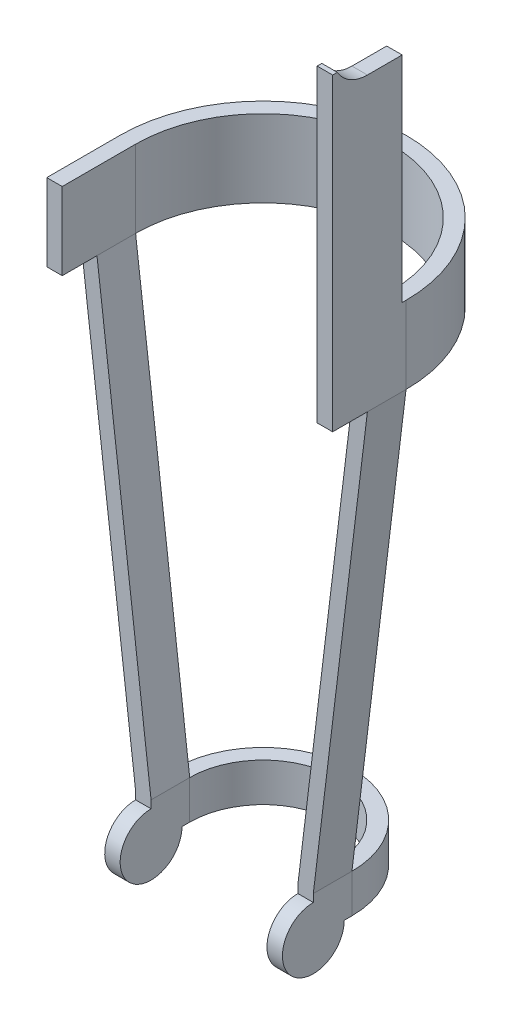
SolidWorks part; units mm, degrees
ref_plane "Front" through (0, 0, 0) normal (0, 0, 1) x (1, 0, 0)
ref_plane "Top" through (0, 0, 0) normal (0, 1, 0) x (1, 0, 0)
ref_plane "Right" through (0, 0, 0) normal (1, 0, 0) x (0, 0, -1)
sketch "草图1" plane through (0, 0, 0) normal (1, 0, 0) x (0, 0, -1)
  line L0 (-38, 0) -> (38, 0)
  line L1 (0, 0) -> (0, 113.6099) construction
  line L2 (0, 0) -> (0, 316)
  line L3 (-66, 270) -> (66, 270)
  line L4 (-15, 316) -> (15, 316)
  dimension "D1" = 38
  dimension "D2" = 76
  dimension "D3" = 132
  dimension "D4" = 66
  dimension "D5" = 270
  dimension "D6" = 30
  dimension "D7" = 15
sketch "草图2" plane through (0, 0, 0) normal (0, 1, 0) x (1, 0, 0)
  line L0 (-46, 0) -> (46, 0) construction
  line L1 (0, 46) -> (0, -46) construction
  line L4 (-46, 0) -> (-46, -20)
  line L5 (-46, -20) -> (-38, -20)
  line L6 (-38, 0) -> (-38, -20)
  line L8 (46, 0) -> (46, -20)
  line L9 (46, -20) -> (38, -20)
  line L10 (38, 0) -> (38, -20)
  arc A0 (38, 0) -> (-38, 0) centre (0, 0) ccw
  arc A1 (46, 0) -> (-46, 0) centre (0, 0) ccw
  dimension "D4" = 20
  dimension "D6" = 20
  dimension "D7" = 8
extrude "凸台-拉伸1" add sketch "草图2" along normal blind 20
sketch "草图3" plane through (-46, 0, 0) normal (-1, 0, 0) x (0, 0, 1)
  circle A0 centre (20, 0) radius 16
extrude "凸台-拉伸2" add sketch "草图3" against normal blind 8
sketch "草图4" plane through (46, 0, 0) normal (1, 0, 0) x (0, 0, -1)
  circle A0 centre (-20, 0) radius 16
extrude "凸台-拉伸3" add sketch "草图4" against normal blind 8
sketch3d "3D草图1"
  line L0 (0, 270, 66) -> (0, 270, -66) construction
  line L1 (0, 0, 0) -> (0, 316, 0) construction
  line L2 (0, 270, 74) -> (0, 270, -74) construction
  line L4 (-74, 270, 0) -> (-74, 270, 20)
  line L5 (-74, 270, 20) -> (-66, 270, 20)
  line L6 (-66, 270, 0) -> (-66, 270, 20)
  line L8 (74, 270, 0) -> (74, 270, 20)
  line L9 (74, 270, 20) -> (66, 270, 20)
  line L10 (66, 270, 0) -> (66, 270, 20)
  arc A0 (-66, 270, 0) -> (66, 270, 0) centre (0, 270, 0) ccw
  arc A1 (-74, 270, 0) -> (74, 270, 0) centre (0, 270, 0) ccw
  point P6 (0, 204, 0)
  point P9 (0, 196, 0)
  dimension "D1" = 20
  dimension "D2" = 8
  dimension "D3" = 20
  dimension "D4" = 8
extrude "凸台-拉伸4" add sketch "3D草图1" along direction (0, 1, 0) on the side of the normal mid plane 40 separate body
sketch "草图5" plane through (0, 20, 0) normal (0, 1, 0) x (1, 0, 0)
  line L1 (46, -20) -> (38, -20)
  line L2 (46, -20) -> (46, 0)
  line L3 (46, 0) -> (38, 0)
  line L4 (38, -20) -> (38, 0)
sketch "草图6" plane through (0, 0, 20) normal (0, 0, 1) x (1, 0, 0)
  line L0 (46, 20) -> (74, 250)
sweep "扫描1" add profiles "草图5" path "草图6"
sketch "草图7" plane through (0, 20, 0) normal (0, 1, 0) x (1, 0, 0)
  line L1 (-46, -20) -> (-38, -20)
  line L2 (-46, -20) -> (-46, 0)
  line L3 (-46, 0) -> (-38, 0)
  line L4 (-38, -20) -> (-38, 0)
sketch "草图8" plane through (0, 0, 20) normal (0, 0, 1) x (1, 0, 0)
  line L0 (-46, 20) -> (-74, 250)
sweep "扫描2" add profiles "草图7" path "草图8"
sketch "草图10" plane through (0, 250, 0) normal (0, -1, 0) x (1, 0, 0)
  line L0 (-74, 20) -> (74, 20) construction
  line L1 (-74, 20) -> (-74, 0) construction
  line L2 (-74, 2) -> (-66, 2)
  line L3 (-74, 2) -> (-74, 38)
  line L4 (-74, 38) -> (-66, 38)
  line L5 (-66, 2) -> (-66, 38)
  line L7 (74, 38) -> (66, 38)
  line L8 (74, 38) -> (74, 2)
  line L9 (74, 2) -> (66, 2)
  line L10 (66, 38) -> (66, 2)
  dimension "D1" = 36
  dimension "D2" = 18
  dimension "D3" = 8
  dimension "D4" = 36
  dimension "D5" = 18
  dimension "D6" = 8
extrude "凸台-拉伸5" add sketch "草图10" against normal blind 160
sketch "草图12" plane through (-74, 0, 0) normal (-1, 0, 0) x (0, 0, 1)
  line L0 (20, 410) -> (20, 441.6329) construction
  line L1 (38, 410) -> (2, 410) construction
  line L2 (2, 410) -> (38, 410) construction
  line L3 (20, 401) -> (2, 401)
  line L4 (2, 410) -> (2, 290) construction
  line L5 (2, 401) -> (2, 419)
  arc A0 (20, 401) -> (2, 419) centre (20, 419) ccw
  dimension "D1" = 9
extrude "切除-拉伸3" cut sketch "草图12" against normal blind 160
sketch "草图13" plane through (-74, 0, 0) normal (-1, 0, 0) x (0, 0, 1)
  line L0 (0, 290) -> (-74, 290) construction
  line L1 (-5.7962, 290) -> (56.403, 290)
  line L2 (-5.7962, 290) -> (-5.7962, 426.5376)
  line L3 (-5.7962, 426.5376) -> (56.403, 426.5376)
  line L4 (56.403, 290) -> (56.403, 426.5376)
extrude "切除-拉伸4" cut sketch "草图13" against normal blind 10
